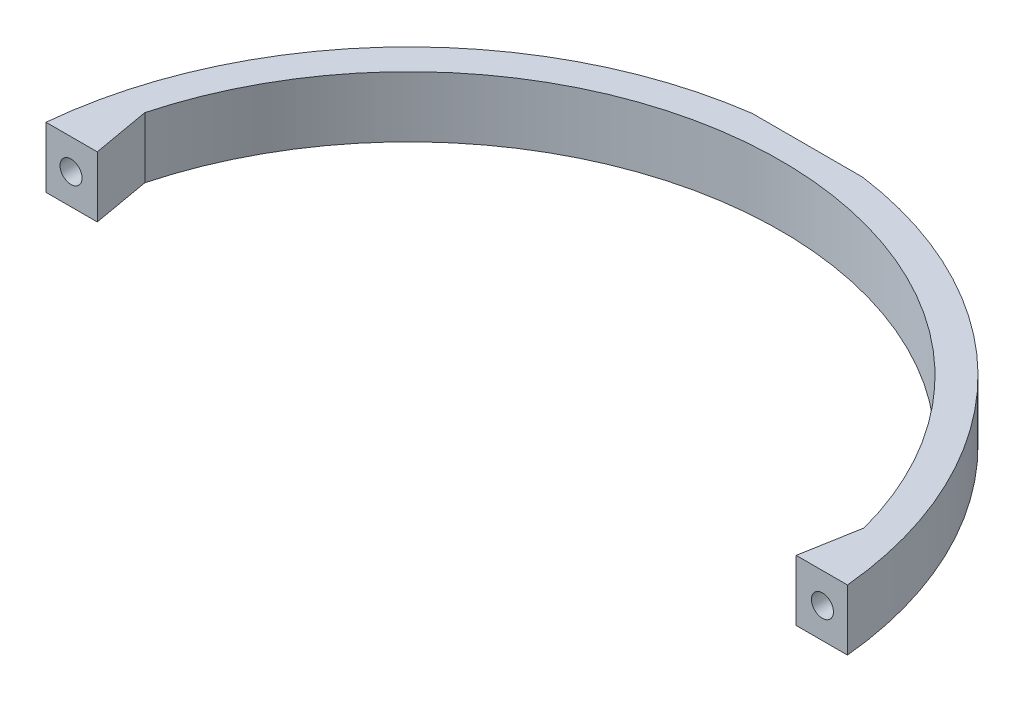
SolidWorks part; units mm, degrees
ref_plane "Front Plane" through (0, 0, 0) normal (0, 0, 1) x (1, 0, 0)
ref_plane "Top Plane" through (0, 0, 0) normal (0, 1, 0) x (1, 0, 0)
ref_plane "Right Plane" through (0, 0, 0) normal (1, 0, 0) x (0, 0, -1)
sketch "Sketch1" plane through (0, 0, 0) normal (0, 1, 0) x (1, 0, 0)
  line L0 (0, 0) -> (-106.8087, 0) construction
  line L1 (52.7636, 5) -> (46.0136, 5)
  line L2 (0, 0) -> (0, 52.5) construction
  line L3 (-52.7636, 5) -> (-46.0136, 5)
  line L4 (0, 0) -> (0, 5) construction
  line L5 (0, 5) -> (12.4808, 5) construction
  line L6 (-7.2629, 52.5) -> (7.2629, 52.5)
  line L7 (46.0136, 5) -> (47.3531, 12.5968)
  line L8 (-46.0136, 5) -> (-47.3531, 12.5968)
  arc A1 (-52.7636, 5) -> (-7.2629, 52.5) centre (0, 0) cw
  arc A2 (-47.3531, 12.5968) -> (47.3531, 12.5968) centre (0, 0) cw
  arc A3 (7.2629, 52.5) -> (52.7636, 5) centre (0, 0) cw
  dimension "D1" = 53
  dimension "D2" = 49
  dimension "D4" = 5
  dimension "D3" = 52.5
  dimension "D5" = 6.75
  dimension "D6" = 6.75
  dimension "D7" = 80
  dimension "D8" = 80
extrude "Boss-Extrude1" add sketch "Sketch1" along normal blind 8
sketch "Sketch4" plane through (0, 0, -52.5) normal (0, 0, -1) x (-1, 0, 0)
  line L0 (-7.2629, 4) -> (0, 4) construction
  line L1 (-7.2629, 8) -> (7.2629, 8) construction
  line L2 (-7.2629, 8) -> (-7.2629, 0) construction
  line L3 (-7.2629, 0) -> (7.2629, 0) construction
  line L4 (7.2629, 8) -> (7.2629, 0) construction
  line L5 (0, 4) -> (0, 8) construction
  line L6 (0, 4) -> (0, 0) construction
  line L7 (0, 4) -> (7.2629, 4) construction
  circle A0 centre (0, 4) radius 3.025
  dimension "D1" = 6.05
extrude "Cut-Extrude3" cut sketch "Sketch4" against normal blind 2.1
sketch "Sketch5" plane through (0, 0, -5) normal (0, 0, 1) x (1, 0, 0)
  line L0 (0, 0) -> (-49.47, 0) construction
  line L1 (-52.7636, 0) -> (-46.0136, 0) construction
  line L2 (-49.47, 0) -> (-49.47, 8) construction
  line L3 (-52.7636, 8) -> (-46.0136, 8) construction
  circle A0 centre (-49.47, 4) radius 1.45
  dimension "D2" = 2.9
  dimension "D1" = 49.47
extrude "Cut-Extrude4" cut sketch "Sketch5" against normal blind 6.5
mirror "Mirror1" about plane through (0, 0, 0) normal (1, 0, 0) of "Cut-Extrude4"
sketch "Sketch6" plane through (0, 0, -50.4) normal (0, 0, -1) x (-1, 0, 0)
  circle A0 centre (0, 4) radius 1.75
  dimension "D1" = 3.5
extrude "Cut-Extrude5" cut sketch "Sketch6" against normal blind 0.41
